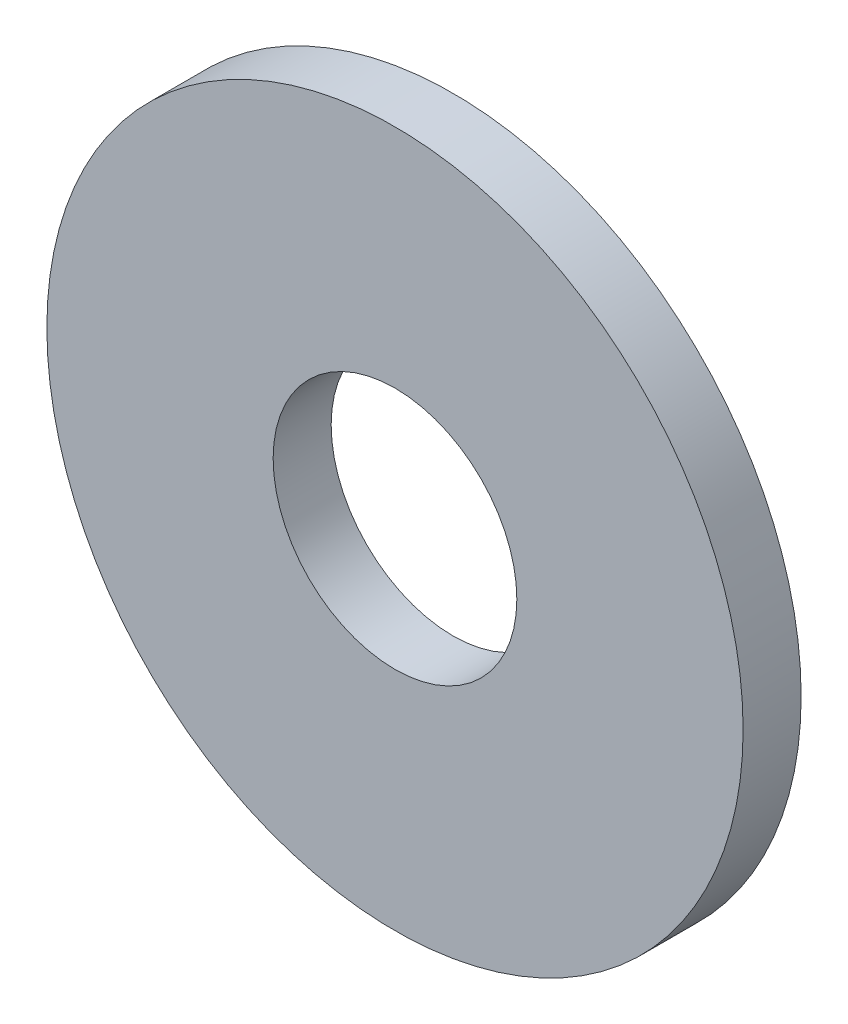
SolidWorks part; units mm, degrees
ref_plane "Plane1" through (0, 0, 0) normal (0, 0, 1) x (1, 0, 0)
ref_plane "Plane2" through (0, 0, 0) normal (0, 1, 0) x (1, 0, 0)
ref_plane "Plane3" through (0, 0, 0) normal (1, 0, 0) x (0, 0, -1)
extrude "Основание-Вытянуть" add sketch "Эскиз1" along normal blind 5
sketch "Эскиз1" plane through (0, 0, 0) normal (0, 0, 1) x (1, 0, 0)
  circle A0 centre (0, 0) radius 30
  circle A1 centre (0, 0) radius 10.5
  dimension "DН" = 60
  dimension "DВ" = 21
